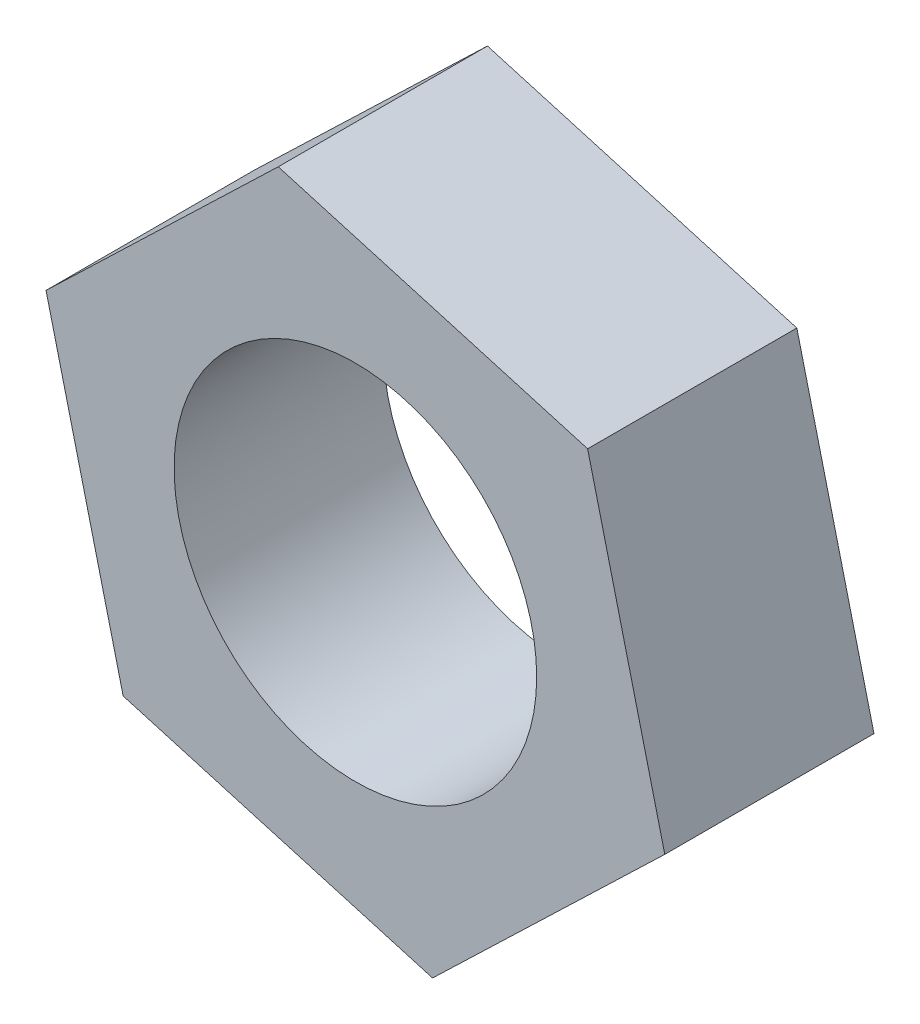
SolidWorks part; units mm, degrees
ref_plane "Alzado" through (0, 0, 0) normal (0, 0, 1) x (1, 0, 0)
ref_plane "Planta" through (0, 0, 0) normal (0, 1, 0) x (1, 0, 0)
ref_plane "Vista lateral" through (0, 0, 0) normal (1, 0, 0) x (0, 0, -1)
sketch "Croquis1" plane through (0, 0, 0) normal (0, 0, 1) x (1, 0, 0)
  line L1 (1.1063, -4.4844) -> (4.4367, -1.2841)
  line L2 (4.4367, -1.2841) -> (3.3304, 3.2002)
  line L3 (3.3304, 3.2002) -> (-1.1063, 4.4844)
  line L4 (-1.1063, 4.4844) -> (-4.4367, 1.2841)
  line L5 (-4.4367, 1.2841) -> (-3.3304, -3.2002)
  line L6 (-3.3304, -3.2002) -> (1.1063, -4.4844)
  circle A0 centre (0, 0) radius 2.6
  circle A1 centre (0, 0) radius 4 construction
  dimension "D1" = 5.2
  dimension "D2" = 8
extrude "Saliente-Extruir1" add sketch "Croquis1" along normal blind 3
